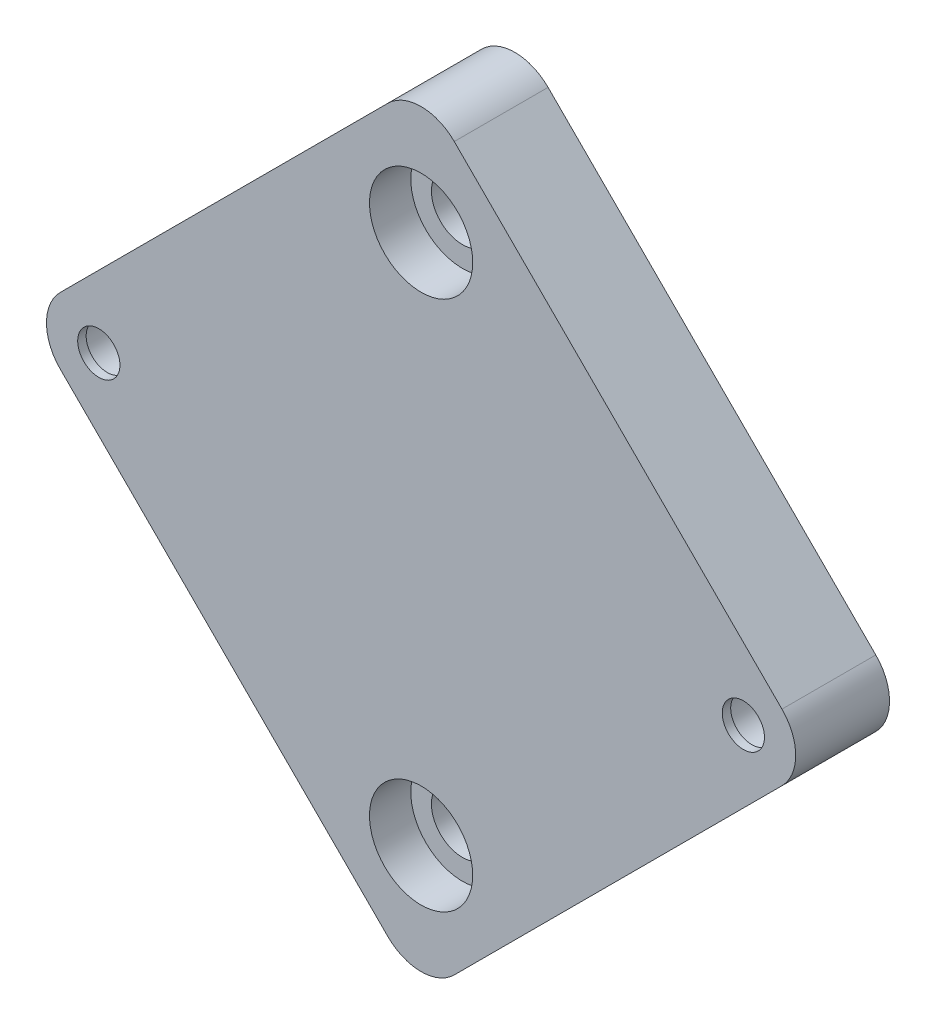
SolidWorks part; units mm, degrees
ref_plane "Front Plane" through (0, 0, 0) normal (0, 0, 1) x (1, 0, 0)
ref_plane "Top Plane" through (0, 0, 0) normal (0, 1, 0) x (1, 0, 0)
ref_plane "Right Plane" through (0, 0, 0) normal (1, 0, 0) x (0, 0, -1)
sketch "Sketch1" plane through (0, 0, 0) normal (0, 0, 1) x (1, 0, 0)
  line L0 (-42, 0) -> (0, 42)
  line L1 (-42, 0) -> (0, -42)
  line L2 (0, 42) -> (42, 0)
  line L3 (0, -42) -> (42, 0)
  line L4 (-42, 0) -> (42, 0) construction
  line L5 (0, 42) -> (0, -42) construction
  circle A0 centre (-34.35, 0) radius 2.25
  circle A1 centre (34.35, 0) radius 2.25
  point P1 (0, 0)
  dimension "D4" = 4.5
  dimension "D5" = 4.5
  dimension "D1" = 84
  dimension "D2" = 68.7
  dimension "D3" = 34.35
extrude "Boss-Extrude1" add sketch "Sketch1" along normal blind 10
sketch "Sketch2" plane through (0, 0, 0) normal (0, 0, 1) x (1, 0, 0)
  circle A0 centre (34.35, 0) radius 2.8
  circle A1 centre (-34.35, 0) radius 2.8
  dimension "D1" = 5.6
  dimension "D2" = 5.6
extrude "Cut-Extrude1" cut sketch "Sketch2" along normal blind 9.1
hole_wizard "CBORE for M6 Hex Socket Head Cap Screw1" positions "3DSketch1" profile "Sketch3" counterbore size "M6" standard "DIN" end condition through all
sketch3d "3DSketch1"
  point P0 (0, 28.2843, 10)
  point P2 (0, -28.2843, 10)
  point P19 (55.2836, 20.9805, 0)
  dimension "D1" = 30
  dimension "D2" = 30
sketch "Sketch3" plane through (0, 28.2843, 10) normal (1, 0, 0) x (0, -1, 0)
  line L0 (0, 0) -> (0, 10)
  line L1 (0, 10) -> (3.3, 10)
  line L3 (3.3, 10) -> (3.3, 4.4)
  line L4 (3.3, 4.4) -> (5.5, 4.4)
  line L5 (5.5, 4.4) -> (5.5, 0)
  line L7 (5.5, 0) -> (0, 0)
  line L11 (0, -6.35) -> (0, 107.95) construction
  dimension "Thru Hole Dia." = 6.6
  dimension "Thru Hole Depth" = 10
  dimension "C'Bore Dia." = 11
  dimension "C'Bore Depth" = 4.4
fillet "Fillet2" radius 5 4 edges at (0, -42, 5) (42, 0, 5) (-42, 0, 5) (0, 42, 5)
